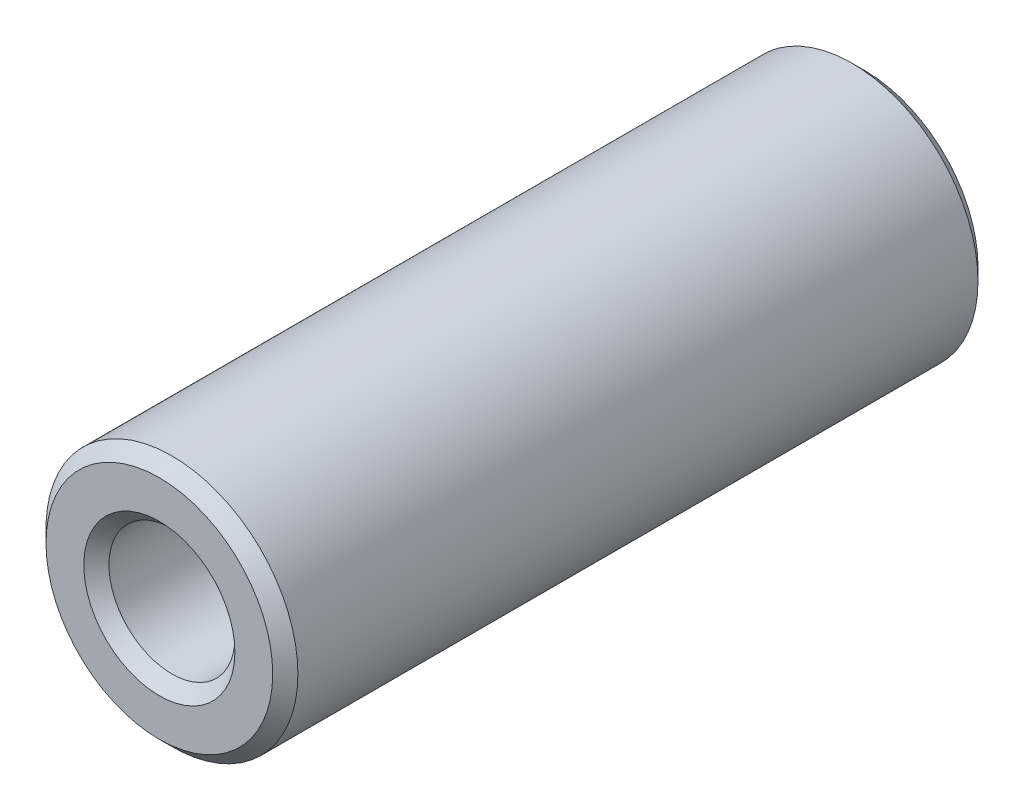
SolidWorks part; units mm, degrees
material "AISI 4140 Steel, quenched & tempered"
ref_plane "Front Plane" through (0, 0, 0) normal (1, 0, 0) x (0, 1, 0)
ref_plane "Top Plane" through (0, 0, 0) normal (0, 0, 1) x (0, 1, 0)
ref_plane "Right Plane" through (0, 0, 0) normal (0, 1, 0) x (-1, 0, 0)
sketch "Sketch1" plane through (0, 0, 0) normal (0, 0, 1) x (0, 1, 0)
  circle A0 centre (0, 0) radius 5
  circle A1 centre (0, 0) radius 2.5
  dimension "D1" = 10
  dimension "D2" = 5
extrude "Boss-Extrude1" add sketch "Sketch1" along normal mid plane 28
chamfer "Chamfer1" distance 0.5 angle 45 4 edges at (5, 0, -14) (5, 0, 14) (2.5, 0, -14) (2.5, 0, 14)
